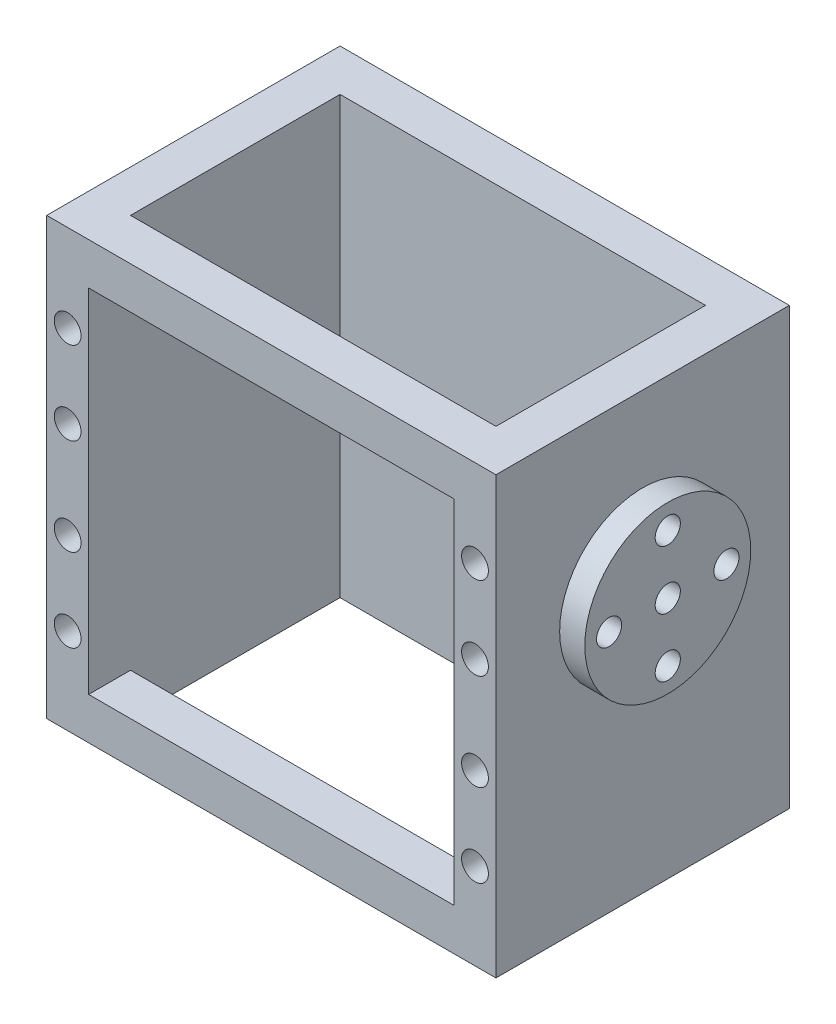
SolidWorks part; units mm, degrees
ref_plane "Front Plane" through (0, 0, 0) normal (0, 0, 1) x (1, 0, 0)
ref_plane "Top Plane" through (0, 0, 0) normal (0, 1, 0) x (1, 0, 0)
ref_plane "Right Plane" through (0, 0, 0) normal (1, 0, 0) x (0, 0, -1)
sketch "Sketch1" plane through (0, 0, 0) normal (0, 1, 0) x (1, 0, 0)
  line L1 (0, 0) -> (53.6, 0)
  line L2 (0, 0) -> (0, -35)
  line L3 (0, -35) -> (53.6, -35)
  line L4 (53.6, 0) -> (53.6, -35)
  line L5 (5, -5) -> (48.6, -5)
  line L6 (5, -5) -> (5, -30)
  line L7 (5, -30) -> (48.6, -30)
  line L8 (48.6, -5) -> (48.6, -30)
  dimension "D1" = 35
  dimension "D2" = 5
  dimension "D3" = 43.6
  dimension "D4" = 5
  dimension "D5" = 25
  dimension "D6" = 5
extrude "Boss-Extrude1" add sketch "Sketch1" along normal blind 52
sketch "Sketch2" plane through (0, 0, 35) normal (0, 0, 1) x (1, 0, 0)
  line L0 (0, 52) -> (0, 0) construction
  line L1 (5, 47) -> (48.6, 47)
  line L2 (5, 47) -> (5, 5)
  line L3 (5, 5) -> (48.6, 5)
  line L4 (48.6, 47) -> (48.6, 5)
  line L5 (53.6, 52) -> (53.6, 0) construction
  line L6 (0, 0) -> (53.6, 0) construction
  dimension "D1" = 5
  dimension "D2" = 5
  dimension "D3" = 5
  dimension "D4" = 42
extrude "Cut-Extrude1" cut sketch "Sketch2" against normal blind 5
sketch "Sketch3" plane through (0, 0, 35) normal (0, 0, 1) x (1, 0, 0)
  line L0 (6.8, 25.5) -> (46.8, 25.5)
  line L1 (6.8, 25.5) -> (6.8, 5)
  line L2 (6.8, 5) -> (46.8, 5)
  line L3 (46.8, 25.5) -> (46.8, 5)
  line L4 (6.8, 15.25) -> (46.8, 15.25) construction
  line L5 (26.8, 25.5) -> (26.8, 5) construction
  line L6 (5, 5) -> (48.6, 5) construction
  line L7 (0, 52) -> (0, 0) construction
  line L8 (53.6, 60.3238) -> (53.6, -14.2444) construction
  line L9 (6.8, 46.9) -> (46.8, 46.9)
  line L10 (6.8, 46.9) -> (6.8, 26.4)
  line L11 (6.8, 26.4) -> (46.8, 26.4)
  line L12 (46.8, 46.9) -> (46.8, 26.4)
  line L13 (6.8, 36.65) -> (46.8, 36.65) construction
  line L14 (26.8, 46.9) -> (26.8, 26.4) construction
  line L15 (53.6, 81.7238) -> (53.6, 7.1556) construction
  circle A0 centre (51.1, 20.2) radius 1.6
  circle A1 centre (51.1, 10.3) radius 1.6
  circle A2 centre (2.5, 10.3) radius 1.6
  circle A3 centre (2.5, 20.2) radius 1.6
  circle A4 centre (51.1, 41.6) radius 1.6
  circle A5 centre (51.1, 31.7) radius 1.6
  circle A6 centre (2.5, 31.7) radius 1.6
  circle A7 centre (2.5, 41.6) radius 1.6
  dimension "D3" = 3.2
  dimension "D4" = 3.2
  dimension "D5" = 3.2
  dimension "D6" = 3.2
  dimension "D21" = 3.2
  dimension "D22" = 3.2
  dimension "D23" = 3.2
  dimension "D24" = 3.2
  dimension "D1" = 40
  dimension "D2" = 20.5
  dimension "D7" = 9.9
  dimension "D8" = 9.9
  dimension "D9" = 48.6
  dimension "D10" = 48.6
  dimension "D11" = 24.3
  dimension "D12" = 24.3
  dimension "D13" = 24.3
  dimension "D14" = 5.3
  dimension "D15" = 0
  dimension "D16" = 2.5
  dimension "D17" = 2.5
  dimension "D18" = 53.6
  dimension "D19" = 40
  dimension "D20" = 20.5
  dimension "D25" = 9.9
  dimension "D26" = 9.9
  dimension "D27" = 48.6
  dimension "D28" = 48.6
  dimension "D29" = 24.3
  dimension "D30" = 24.3
  dimension "D31" = 24.3
  dimension "D32" = 5.3
  dimension "D33" = 2.5
  dimension "D34" = 2.5
  dimension "D35" = 11.5
extrude "Cut-Extrude2" cut sketch "Sketch3" against normal blind 5
sketch "Sketch4" plane through (53.6, 0, 0) normal (1, 0, 0) x (0, 0, -1)
  line L0 (-35, 52) -> (0, 52) construction
  line L1 (0, 52) -> (0, 0) construction
  line L2 (-35, 52) -> (-35, 0) construction
  circle A0 centre (-17.5, 32) radius 9.9
  circle A1 centre (-17.5, 39) radius 1.5
  circle A2 centre (-10.5, 32) radius 1.5
  circle A3 centre (-17.5, 25) radius 1.5
  circle A4 centre (-24.5, 32) radius 1.5
  circle A5 centre (-17.5, 32) radius 1.5
  dimension "D1" = 3
  dimension "D2" = 3
  dimension "D3" = 3
  dimension "D4" = 3
  dimension "D5" = 3
  dimension "D6" = 19.8
  dimension "D11" = 20
  dimension "D7" = 14
  dimension "D8" = 7
  dimension "D9" = 14
  dimension "D10" = 7
  dimension "D12" = 17.5
  dimension "D13" = 17.5
extrude "Boss-Extrude2" add sketch "Sketch4" along normal blind 3
sketch "Sketch5" plane through (48.6, 0, 0) normal (-1, 0, 0) x (0, 0, 1)
  circle A0 centre (17.5, 32) radius 9.9
  dimension "D1" = 19.8
extrude "Cut-Extrude3" cut sketch "Sketch5" against normal blind 5
sketch "Sketch6" plane through (0, 0, 0) normal (-1, 0, 0) x (0, 0, 1)
  circle A0 centre (17.5, 32) radius 5
  dimension "D1" = 10
extrude "Boss-Extrude3" add sketch "Sketch6" along normal blind 5
